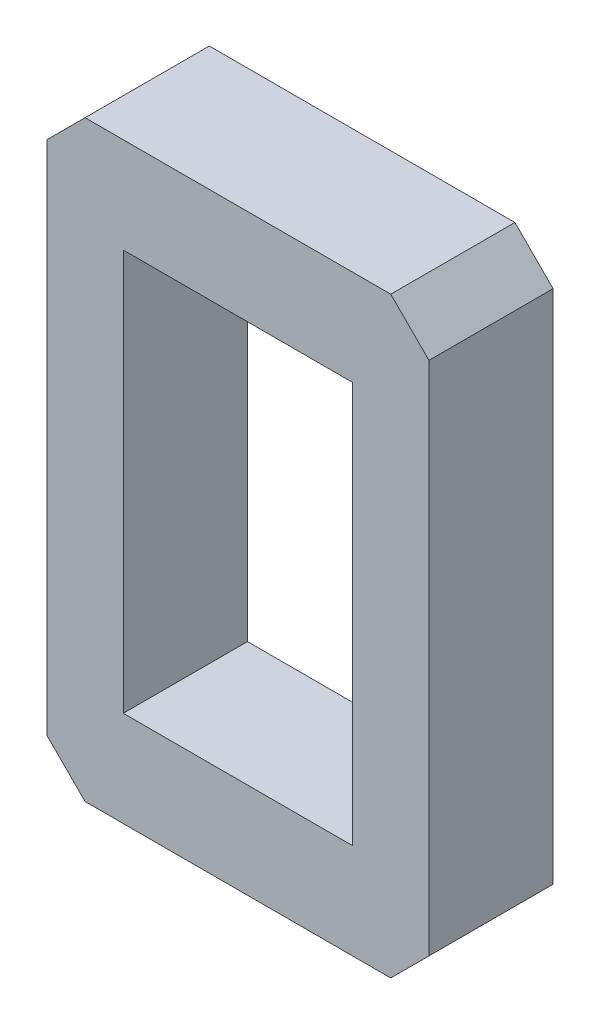
SolidWorks part; units mm, degrees
ref_plane "Front Plane" through (0, 0, 0) normal (0, 0, 1) x (1, 0, 0)
ref_plane "Top Plane" through (0, 0, 0) normal (0, 1, 0) x (1, 0, 0)
ref_plane "Right Plane" through (0, 0, 0) normal (1, 0, 0) x (0, 0, -1)
sketch "Sketch1" plane through (0, 0, 0) normal (0, 0, 1) x (1, 0, 0)
  line L1 (-10, 15.5) -> (10, 15.5)
  line L2 (-10, 15.5) -> (-10, -15.5)
  line L3 (-10, -15.5) -> (10, -15.5)
  line L4 (10, 15.5) -> (10, -15.5)
  line L5 (-10, 15.5) -> (10, -15.5) construction
  line L6 (-10, -15.5) -> (10, 15.5) construction
  line L7 (-6, 10.5) -> (6, 10.5)
  line L8 (-6, 10.5) -> (-6, -10.5)
  line L9 (-6, -10.5) -> (6, -10.5)
  line L10 (6, 10.5) -> (6, -10.5)
  line L11 (-6, 10.5) -> (6, -10.5) construction
  line L12 (-6, -10.5) -> (6, 10.5) construction
  point P0 (0, 0)
  point P6 (0, 0)
  dimension "D1" = 31
  dimension "D2" = 20
  dimension "D3" = 21
  dimension "D4" = 12
extrude "Boss-Extrude1" add sketch "Sketch1" along normal blind 6.5 contours L4 L1 L2 L3 L7 L10 L9 L8
chamfer "Chamfer1" distance 2 angle 45 4 edges at (10, -15.5, 3.25) (-10, -15.5, 3.25) (-10, 15.5, 3.25) (10, 15.5, 3.25)
